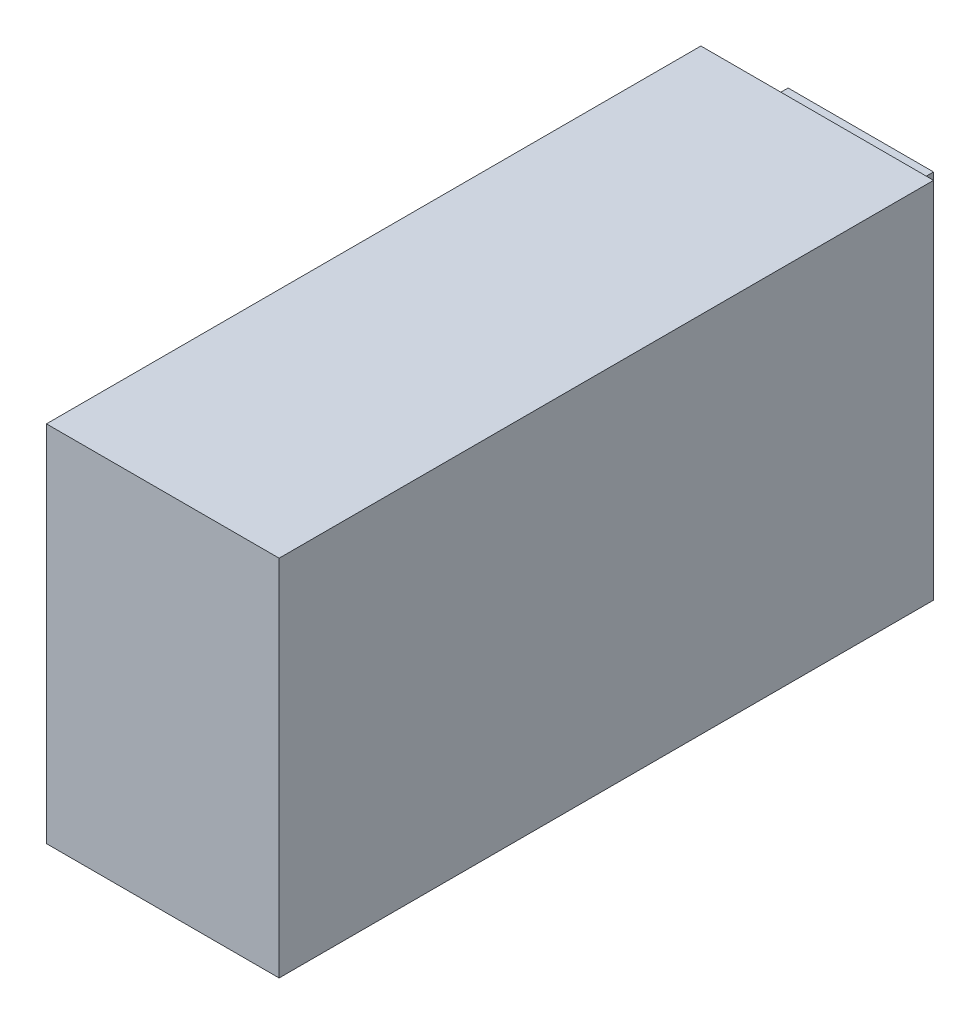
SolidWorks part; units mm, degrees
ref_plane "Front Plane" through (0, 0, 0) normal (0, 0, 1) x (1, 0, 0)
ref_plane "Top Plane" through (0, 0, 0) normal (0, 1, 0) x (1, 0, 0)
ref_plane "Right Plane" through (0, 0, 0) normal (1, 0, 0) x (0, 0, -1)
sketch "Sketch1" plane through (0, 0, 0) normal (0, 1, 0) x (1, 0, 0)
  line L1 (0, 0) -> (16, 0)
  line L2 (0, 0) -> (0, 45)
  line L3 (0, 45) -> (16, 45)
  line L4 (16, 0) -> (16, 45)
  dimension "D1" = 16
  dimension "D2" = 45
extrude "Boss-Extrude1" add sketch "Sketch1" along normal blind 25
sketch "Sketch2" plane through (0, 0, -45) normal (0, 0, -1) x (-1, 0, 0)
  line L0 (0, 25) -> (0, 0) construction
  line L1 (-13, 22.5) -> (-3, 22.5)
  line L2 (-13, 22.5) -> (-13, 2.5)
  line L3 (-13, 2.5) -> (-3, 2.5)
  line L4 (-3, 22.5) -> (-3, 2.5)
  line L5 (-16, 25) -> (0, 25) construction
  point P4 (-3, 12.5)
  point P5 (0, 12.5)
  point P6 (-8, 25)
  point P9 (-8, 22.5)
  point P12 (0, 0)
  point P13 (0, 0)
  dimension "D1" = 10
  dimension "D2" = 20
extrude "Boss-Extrude2" add sketch "Sketch2" along normal blind 3
